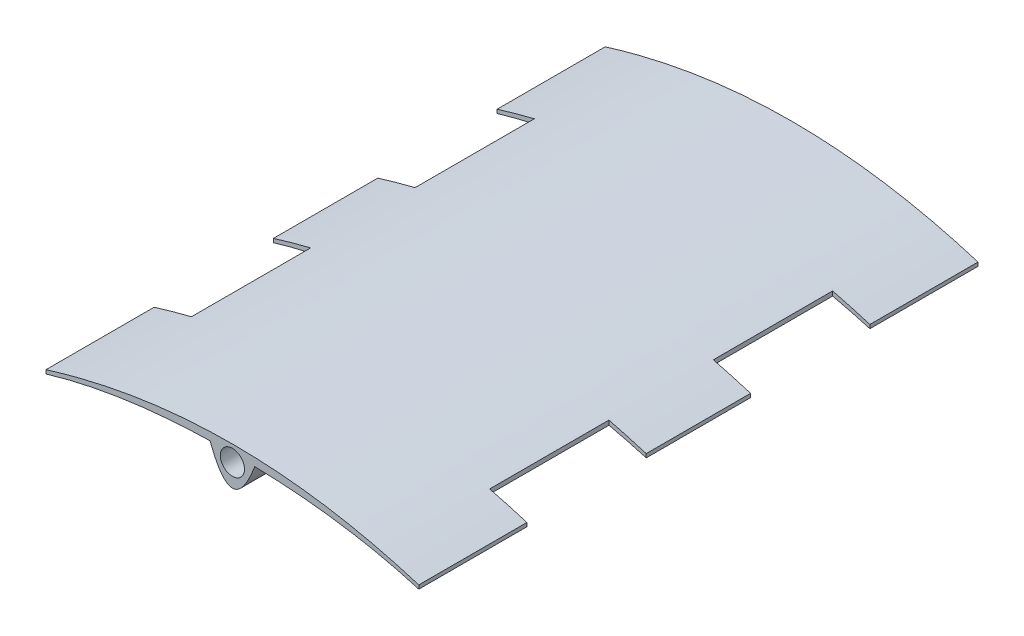
SolidWorks part; units mm, degrees
ref_plane "Front Plane" through (0, 0, 0) normal (0, 0, 1) x (1, 0, 0)
ref_plane "Top Plane" through (0, 0, 0) normal (0, 1, 0) x (1, 0, 0)
ref_plane "Right Plane" through (0, 0, 0) normal (1, 0, 0) x (0, 0, -1)
sketch "草圖1" plane through (0, 0, 0) normal (0, 0, 1) x (1, 0, 0)
  line L0 (-50, -3.4806) -> (0, 12) construction
  line L1 (0, 12) -> (50, -3.4806) construction
  line L2 (-50, -3.4806) -> (-50, -4.4806)
  line L3 (50, -3.4806) -> (50, -4.4806)
  line L4 (-6, 2) -> (0, -14) construction
  line L5 (0, -14) -> (6, 2) construction
  line L6 (6, 2) -> (30, 1.4732) construction
  line L7 (30, 1.4732) -> (50, -4.4806) construction
  line L8 (-6, 2) -> (-30, 1.4732) construction
  line L9 (-30, 1.4732) -> (-50, -4.4806) construction
  circle A0 centre (0, 0) radius 3.25
  spline S0 degree 2 poles (-50, -3.4806) (0, 12) (50, -3.4806) knots 0 0 0 1 1 1
  spline S1 degree 2 poles (-6, 2) (0, -14) (6, 2) knots 0 0 0 1 1 1
  spline S2 degree 2 poles (6, 2) (30, 1.4732) (50, -4.4806) knots 0 0 0 1 1 1
  spline S3 degree 2 poles (-6, 2) (-30, 1.4732) (-50, -4.4806) knots 0 0 0 1 1 1
  dimension "D1" = 6.5
  dimension "D2" = 100
  dimension "D3" = 50
  dimension "D4" = 12
  dimension "D5" = 1
  dimension "D6" = 14
  dimension "D7" = 6
  dimension "D8" = 6
  dimension "D9" = 30
  dimension "D10" = 30
  dimension "D11" = 2
extrude "填料-伸長1" add sketch "草圖1" along normal blind 150
sketch "草圖2" plane through (0, 0, 0) normal (0, 1, 0) x (1, 0, 0)
  line L0 (50, -150) -> (50, 0) construction
  line L1 (-50, -121) -> (-40, -121)
  line L2 (-50, -121) -> (-50, -89)
  line L3 (-50, -89) -> (-40, -89)
  line L4 (-40, -121) -> (-40, -89)
  line L5 (-50, -29) -> (-40, -29)
  line L6 (-50, -29) -> (-50, -61)
  line L7 (-50, -61) -> (-40, -61)
  line L8 (-40, -29) -> (-40, -61)
  line L9 (50, -29) -> (40, -29)
  line L10 (50, -29) -> (50, -61)
  line L11 (50, -61) -> (40, -61)
  line L12 (40, -29) -> (40, -61)
  line L13 (50, -121) -> (40, -121)
  line L14 (50, -121) -> (50, -89)
  line L15 (50, -89) -> (40, -89)
  line L16 (40, -121) -> (40, -89)
  line L17 (-50, -150) -> (-50, 0) construction
  line L18 (50, 0) -> (-50, 0) construction
  line L19 (-50, -150) -> (50, -150) construction
  dimension "D1" = 10
  dimension "D2" = 32
  dimension "D3" = 29
  dimension "D4" = 28
  dimension "D5" = 29
extrude "除料-伸長1" cut sketch "草圖2" against normal through all and the other way through all
